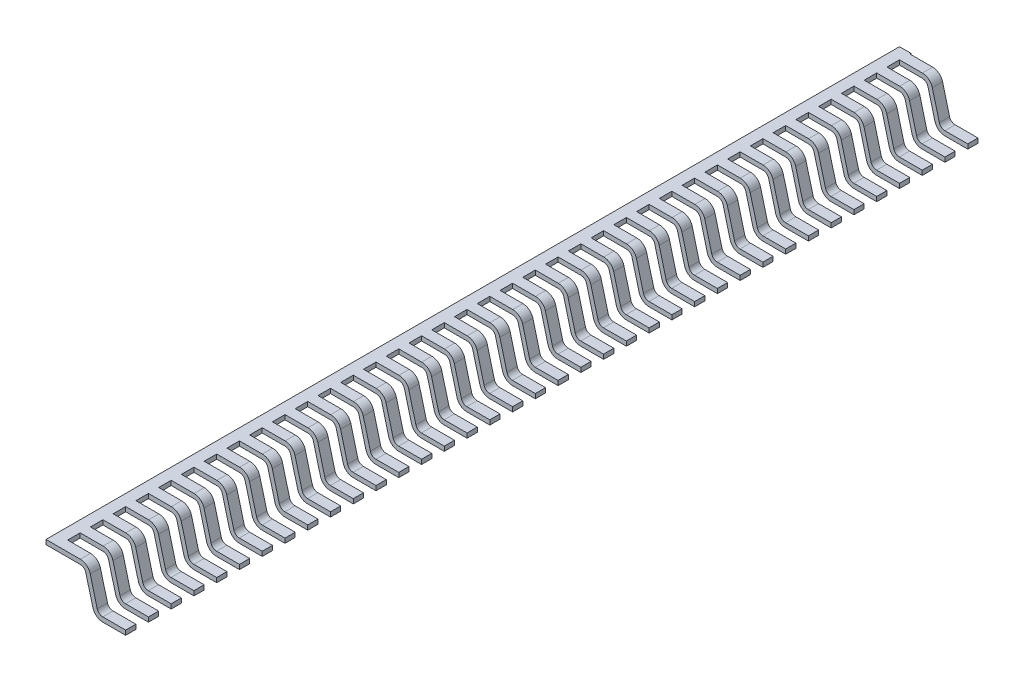
SolidWorks part; units mm, degrees
ref_plane "Front Plane" through (0, 0, 0) normal (0, 0, 1) x (1, 0, 0)
ref_plane "Top Plane" through (0, 0, 0) normal (0, 1, 0) x (1, 0, 0)
ref_plane "Right Plane" through (0, 0, 0) normal (1, 0, 0) x (0, 0, -1)
sketch "Sketch1" plane through (0, 0, 0) normal (0, 0, 1) x (1, 0, 0)
  line L0 (-0.1279, 0.2863) -> (0.0296, -0.3122)
  line L1 (-0.0296, 0.3122) -> (0.1279, -0.2863)
  line L2 (-0.762, 0.4826) -> (-0.762, 0.381)
  line L4 (0.2507, -0.4826) -> (0.762, -0.4826)
  line L5 (-0.762, 0.4826) -> (-0.2507, 0.4826)
  line L7 (-0.762, 0.381) -> (-0.2507, 0.381)
  line L8 (0.2507, -0.381) -> (0.762, -0.381)
  line L9 (0.762, -0.381) -> (0.762, -0.4826)
  arc A0 (-0.1279, 0.2863) -> (-0.2507, 0.381) centre (-0.2507, 0.254) ccw
  arc A1 (0.2507, -0.381) -> (0.1279, -0.2863) centre (0.2507, -0.254) cw
  arc A2 (-0.0296, 0.3122) -> (-0.2507, 0.4826) centre (-0.2507, 0.254) ccw
  arc A3 (0.2507, -0.4826) -> (0.0296, -0.3122) centre (0.2507, -0.254) cw
extrude "Extrude1" add sketch "Sketch1" along normal blind 0.2286
sketch "Sketch2" plane through (0, 0.4826, 0) normal (0, 1, 0) x (-1, 0, 0)
  line L0 (0.762, 0.2286) -> (0.762, -18.8214)
  line L1 (1.016, 0.2286) -> (1.016, -18.8214)
  line L2 (1.016, 0.2286) -> (0.762, 0.2286)
  line L3 (1.016, -18.8214) -> (0.762, -18.8214)
  dimension "D1" = 0.254
  dimension "D2" = 19.05
extrude "Extrude3" add sketch "Sketch2" against normal blind 0.1016
pattern_linear "LPattern2" count 38 spacing 0.508 along (0, 0, -1) of "Extrude1"
